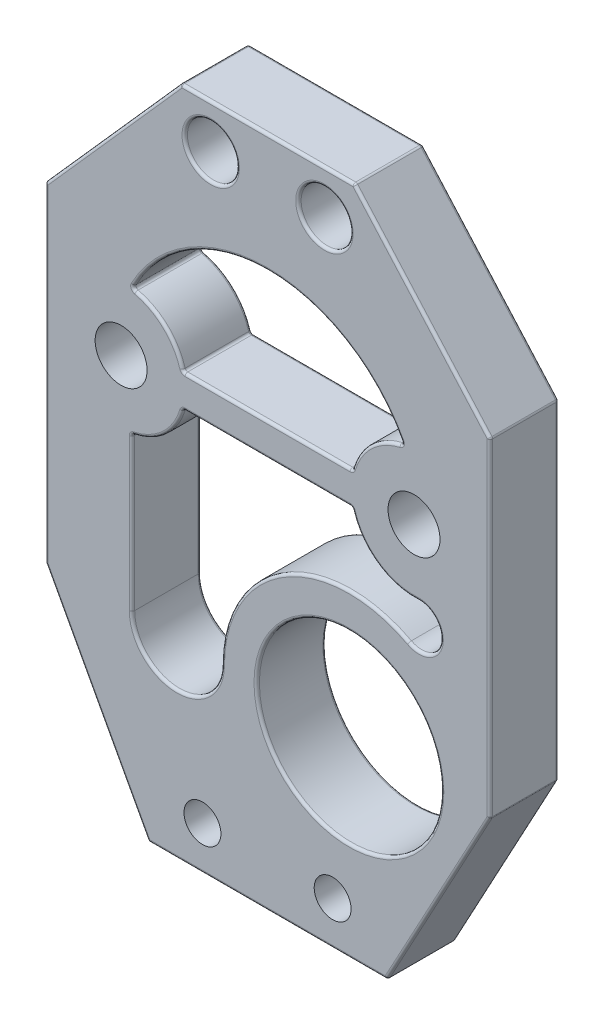
SolidWorks part; units mm, degrees
material "AISI 304"
ref_plane "Plano frontal" through (0, 0, 0) normal (0, 0, 1) x (1, 0, 0)
ref_plane "Plano superior" through (0, 0, 0) normal (0, 1, 0) x (1, 0, 0)
ref_plane "Plano direito" through (0, 0, 0) normal (1, 0, 0) x (0, 0, -1)
sketch "Esboço1" plane through (0, 0, 0) normal (0, 0, 1) x (1, 0, 0)
  line L0 (0, 89.497) -> (0, -48.9301) construction
  line L1 (-7.99, 62) -> (7.99, 62)
  line L2 (-7.99, 62) -> (-20.5, 47.9)
  line L3 (-20.5, 47.9) -> (-20.5, 17.6)
  line L4 (-20.5, 17.6) -> (-11, 0)
  line L5 (-11, 0) -> (11, 0)
  line L6 (20.5, 17.6) -> (11, 0)
  line L7 (20.5, 47.9) -> (20.5, 17.6)
  line L8 (7.99, 62) -> (20.5, 47.9)
  line L9 (-7.7939, 39.1) -> (7.7939, 39.1)
  line L10 (-12.4954, 31.7862) -> (-12.4954, 17.6)
  line L11 (-13.5, 37.6) -> (13.5, 37.6) construction
  line L12 (-7.7939, 36.1) -> (7.7939, 36.1)
  circle A0 centre (5.24, 58) radius 2.395
  circle A1 centre (-5.24, 58) radius 2.395
  circle A2 centre (6, 4) radius 1.5
  circle A3 centre (-6, 4) radius 1.5
  circle A4 centre (7.5, 17.6) radius 8.5
  circle A5 centre (13.5, 37.6) radius 2.395
  circle A6 centre (-13.5, 37.6) radius 2.395
  arc A7 (-12.4954, 31.7862) -> (-7.7939, 36.1) centre (-13.5, 37.6) ccw
  arc A8 (12.4954, 43.4138) -> (7.7939, 39.1) centre (13.5, 37.6) ccw
  arc A9 (-12.4954, 43.4138) -> (12.4954, 43.4138) centre (0, 37.1) cw
  arc A10 (-12.4954, 17.6) -> (-4.2246, 17.6) centre (-8.36, 17.6) ccw
  arc A11 (-4.2246, 17.6) -> (13.0125, 27.9478) centre (7.5, 17.6) cw
  arc A13 (13.0125, 27.9478) -> (13.8382, 31.7097) centre (13.9529, 29.713) ccw
  arc A14 (7.7939, 36.1) -> (13.8382, 31.7097) centre (13.5, 37.6) ccw
  arc A15 (-7.7939, 39.1) -> (-12.4954, 43.4138) centre (-13.5, 37.6) ccw
  point P6 (0, 62)
  point P13 (0, 0)
  point P16 (0, 62)
  dimension "D7" = 4.79
  dimension "D8" = 4
  dimension "D9" = 15.26
  dimension "D10" = 3
  dimension "D11" = 4
  dimension "D12" = 5
  dimension "D13" = 17
  dimension "D14" = 13
  dimension "D15" = 17.6
  dimension "D16" = 4.79
  dimension "D17" = 24.4
  dimension "D18" = 7
  dimension "D19" = 11.8
  dimension "D22" = 14
  dimension "D24" = 2
  dimension "D1" = 11
  dimension "D2" = 12.51
  dimension "D3" = 30.3
  dimension "D4" = 14.1
  dimension "D5" = 17.6
  dimension "D6" = 9.5
  dimension "D20" = 10.9
  dimension "D21" = 12
  dimension "D23" = 12.14
extrude "Ressalto-extrusão1" add sketch "Esboço1" along normal blind 6.35
fillet "Filete1" radius 0.25 63 edges at (-7.99, 62, 3.175) (-20.5, 47.9, 3.175) (7.99, 62, 3.175) (20.5, 47.9, 3.175) (11, 0, 3.175) (20.5, 17.6, 3.175) (0, 62, 6.35) (14.245, 54.95, 6.35) (20.5, 32.75, 6.35) (15.75, 8.8, 6.35) (0, 0, 6.35) (-20.5, 32.75, 6.35) (-14.245, 54.95, 6.35) (0, 36.1, 0) (10.0327, 32.8264, 0) (15.9064, 29.2842, 0) (1.4654, 27.6523, 0) (-8.36, 13.4646, 0) (-12.4954, 24.6931, 0) (-9.5112, 33.2527, 0) (-11.105, 37.6, 0) (15.895, 37.6, 0) (16, 17.6, 0) (7.635, 58, 0) (-2.845, 58, 0) (-20.5, 32.75, 0) (0, 0, 0) (15.75, 8.8, 0) (20.5, 32.75, 0) (14.245, 54.95, 0) (0, 62, 0) (-14.245, 54.95, 0) (0, 51.1, 0) (9.5112, 41.9473, 0) (0, 39.1, 0) (-9.5112, 41.9473, 0) (-20.5, 17.6, 3.175) (-15.75, 8.8, 6.35) (-11, 0, 3.175) (-15.75, 8.8, 0) (-12.4954, 43.4138, 3.175) (9.5112, 41.9473, 6.35) (-9.5112, 41.9473, 6.35) (-9.5112, 33.2527, 6.35) (10.0327, 32.8264, 6.35) (15.9064, 29.2842, 6.35) (1.4654, 27.6523, 6.35) (0, 51.1, 6.35) (12.4954, 43.4138, 3.175) (-12.4954, 24.6931, 6.35) (-12.4954, 31.7862, 3.175) (7.7939, 39.1, 3.175) (0, 39.1, 6.35) (-7.7939, 39.1, 3.175) (-11.105, 37.6, 6.35) (-2.845, 58, 6.35) (7.635, 58, 6.35) (15.895, 37.6, 6.35) (-7.7939, 36.1, 3.175) (0, 36.1, 6.35) (7.7939, 36.1, 3.175) (-8.36, 13.4646, 6.35) (16, 17.6, 6.35)
sketch "草图1" plane through (0, 0, 0) normal (0, 0, 1) x (1, 0, 0)
  line L0 (13.5, 39.995) -> (13.5, 34.955) construction
  line L1 (-7.635, 58) -> (-2.845, 58) construction
  line L2 (4.5, 4) -> (7.5, 4) construction
  circle A0 centre (13.5, 37.6) radius 2.395 construction
  circle A1 centre (13.5, 37.6) radius 2.645 construction
  circle A2 centre (-5.24, 58) radius 2.395 construction
  circle A3 centre (6, 4) radius 1.5 construction
  circle A4 centre (-13.5, 37.6) radius 3.2485
  circle A5 centre (-13.5, 37.6) radius 2.395
  circle A6 centre (13.5, 37.6) radius 3.3226
  circle A7 centre (13.5, 37.6) radius 2.395
  dimension "D1" = 4.79
  dimension "D2" = 4.79
extrude "凸台-拉伸1" add sketch "草图1" along normal up to surface (6.35 mm away) up to face at (7.5, 4, 6.35)
sketch "草图2" plane through (0, 0, 0) normal (0, 0, 1) x (1, 0, 0)
  line L0 (-7.5, 4) -> (-4.5, 4) construction
  line L1 (-4.5, 4) -> (4.5, 4) construction
  line L2 (4.5, 4) -> (7.5, 4) construction
  circle A0 centre (-6, 4) radius 1.5 construction
  circle A1 centre (6, 4) radius 1.5 construction
  circle A2 centre (-6, 4) radius 1.7
  circle A3 centre (6, 4) radius 1.7
  dimension "D1" = 3.4
  dimension "D2" = 3.4
extrude "切除-拉伸1" cut sketch "草图2" along normal up to surface (6.35 mm away) up to face at (7.5, 4, 6.35)
